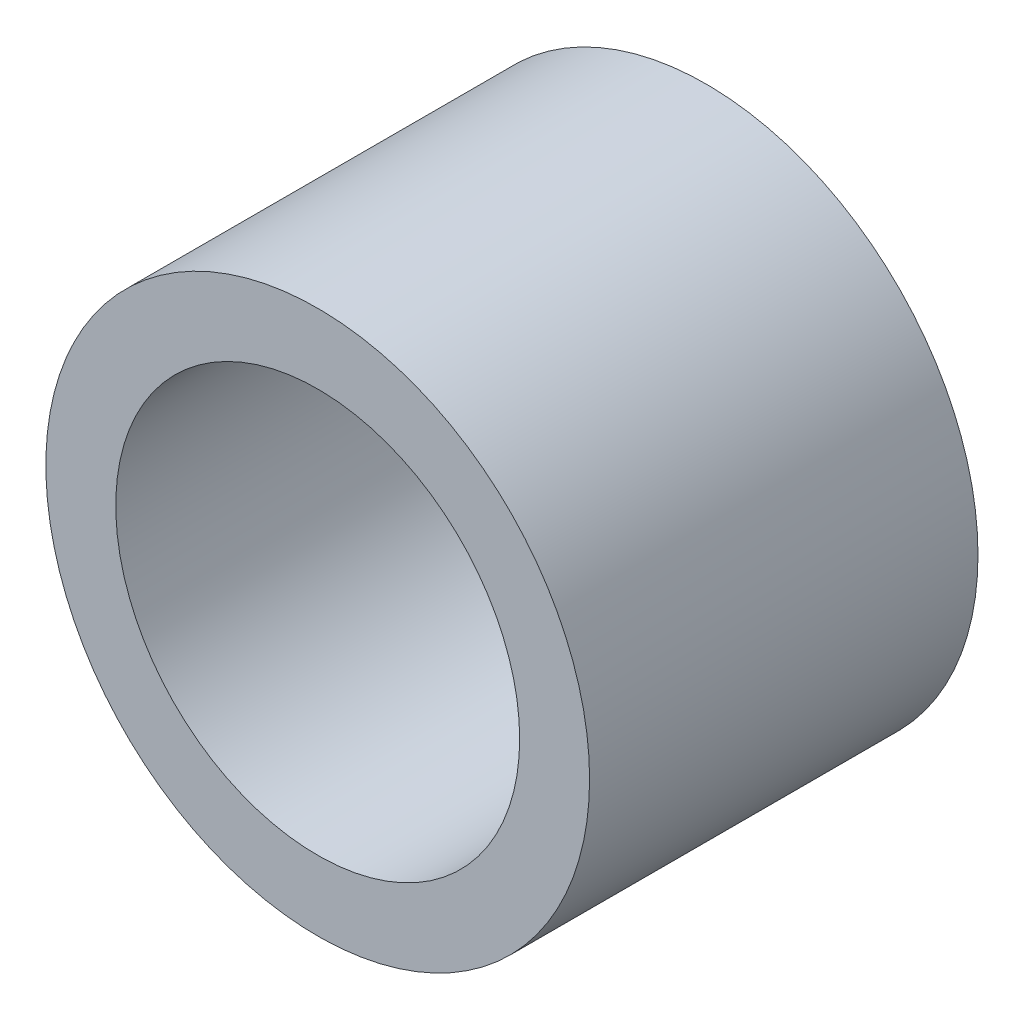
SolidWorks part; units mm, degrees
ref_plane "Front Plane" through (0, 0, 0) normal (0, 0, 1) x (1, 0, 0)
ref_plane "Top Plane" through (0, 0, 0) normal (0, 1, 0) x (1, 0, 0)
ref_plane "Right Plane" through (0, 0, 0) normal (1, 0, 0) x (0, 0, -1)
sketch "ｽｹｯﾁ1" plane through (0, 0, 0) normal (0, 0, 1) x (1, 0, 0)
  circle A0 centre (0, 0) radius 7
  circle A1 centre (0, 0) radius 5.2
  dimension "D1" = 10.4
  dimension "D2" = 14
extrude "ﾎﾞｽ - 押し出し1" add sketch "ｽｹｯﾁ1" along normal blind 10
